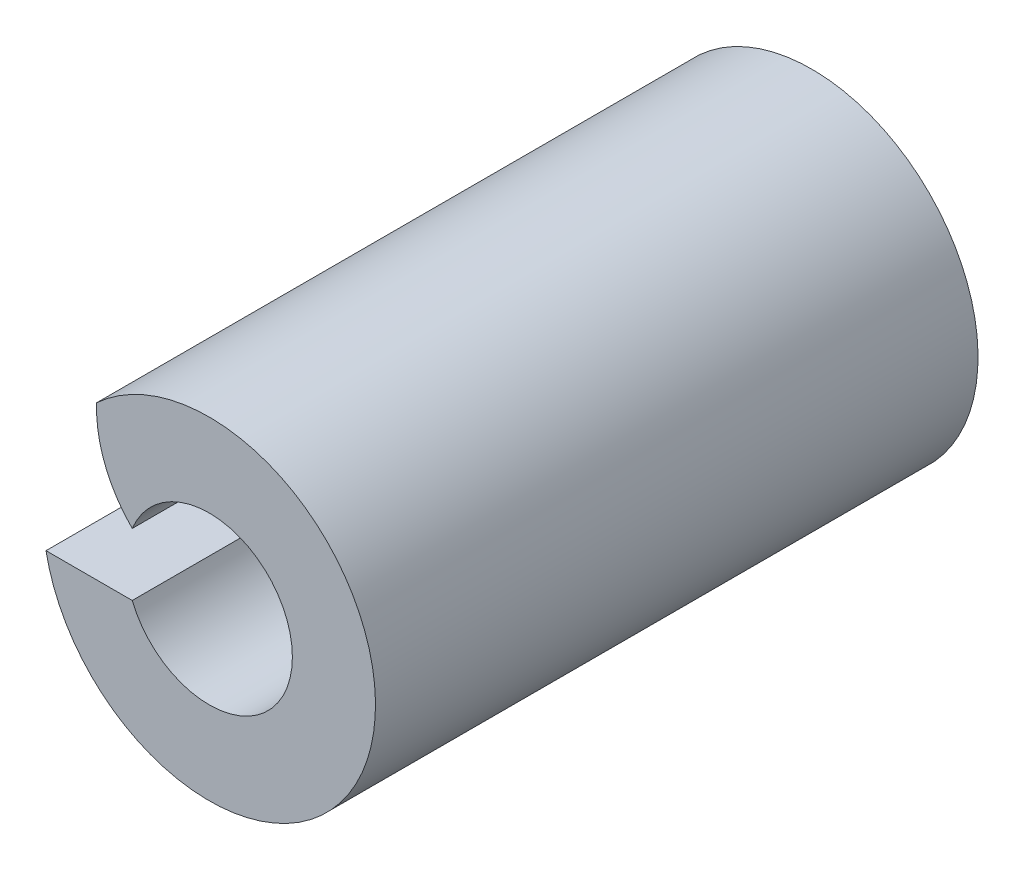
SolidWorks part; units mm, degrees
material "Brass"
ref_plane "Front Plane" through (0, 0, 0) normal (0, 0, 1) x (1, 0, 0)
ref_plane "Top Plane" through (0, 0, 0) normal (0, 1, 0) x (1, 0, 0)
ref_plane "Right Plane" through (0, 0, 0) normal (1, 0, 0) x (0, 0, -1)
sketch "Sketch1" plane through (0, 0, -307.2527) normal (0, 0, 1) x (1, 0, 0)
  line L0 (-0.1827, -19.4362) -> (-0.1827, -22.4362) construction
  line L1 (-0.1827, -19.4362) -> (-4.3327, -19.4362)
  line L3 (3.5254, -5.9362) -> (3.5254, -35.9362) construction
  line L5 (1.5254, -22.4362) -> (1.5254, -19.4362) construction
  line L13 (-4.3327, -22.4362) -> (-0.1827, -22.4362)
  arc A0 (-0.1827, -22.4362) -> (-0.1827, -19.4362) centre (3.5254, -20.9362) ccw
  arc A1 (-4.3327, -22.4362) -> (-4.3327, -19.4362) centre (3.5254, -20.9362) ccw
  circle A2 centre (3.5254, -20.9362) radius 8 construction
  circle A3 centre (3.5254, -20.9362) radius 4 construction
extrude "Boss-Extrude1" add sketch "Sketch1" along normal up to surface (29 mm away)
sketch "Sketch2" plane through (0, 0, -278.2527) normal (0, 0, 1) x (1, 0, 0)
  line L0 (-0.1827, -19.4362) -> (-4.3327, -19.4362)
  line L2 (-1.8941, -15.0516) -> (3.5254, -20.9362) construction
  line L3 (-0.1827, -19.4362) -> (-1.9998, -17.6192) construction
  line L4 (-1.8941, -15.0516) -> (-1.9998, -17.6192) construction
  arc A0 (-4.3327, -19.4362) -> (-1.8941, -15.0516) centre (3.5254, -20.9362) cw
  arc A1 (-0.1827, -19.4362) -> (-1.8941, -15.0516) centre (3.961, -15.2925) cw
  arc A2 (-4.3327, -22.4362) -> (-4.3327, -19.4362) centre (3.5254, -20.9362) ccw construction
  dimension "D1" = 45
  dimension "D2" = 45
extrude "Cut-Extrude1" cut sketch "Sketch2" against normal up to surface (29 mm away) up to face at (3.6339, -20.9362, -307.2527)
